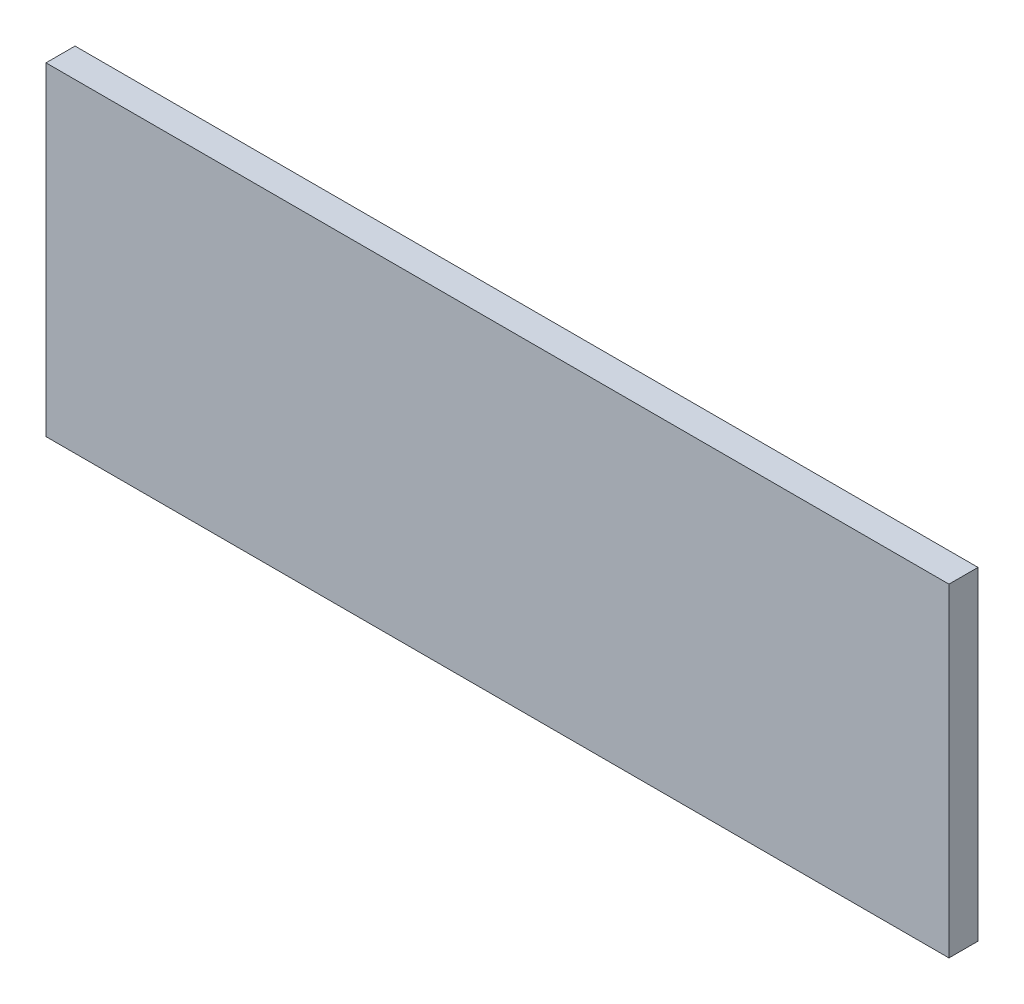
SolidWorks part; units mm, degrees
ref_plane "Plano frontal" through (0, 0, 0) normal (0, 0, 1) x (1, 0, 0)
ref_plane "Plano superior" through (0, 0, 0) normal (0, 1, 0) x (1, 0, 0)
ref_plane "Plano direito" through (0, 0, 0) normal (1, 0, 0) x (0, 0, -1)
sketch "Esboço1" plane through (0, 0, 0) normal (0, 0, 1) x (1, 0, 0)
  line L1 (-31.1, 11.15) -> (31.1, 11.15)
  line L2 (-31.1, 11.15) -> (-31.1, -11.15)
  line L3 (-31.1, -11.15) -> (31.1, -11.15)
  line L4 (31.1, 11.15) -> (31.1, -11.15)
  line L5 (-31.1, 11.15) -> (31.1, -11.15) construction
  line L6 (-31.1, -11.15) -> (31.1, 11.15) construction
  point P0 (0, 0)
  dimension "D1" = 22.3
  dimension "D2" = 62.2
extrude "Ressalto-extrusão1" add sketch "Esboço1" along normal blind 2
